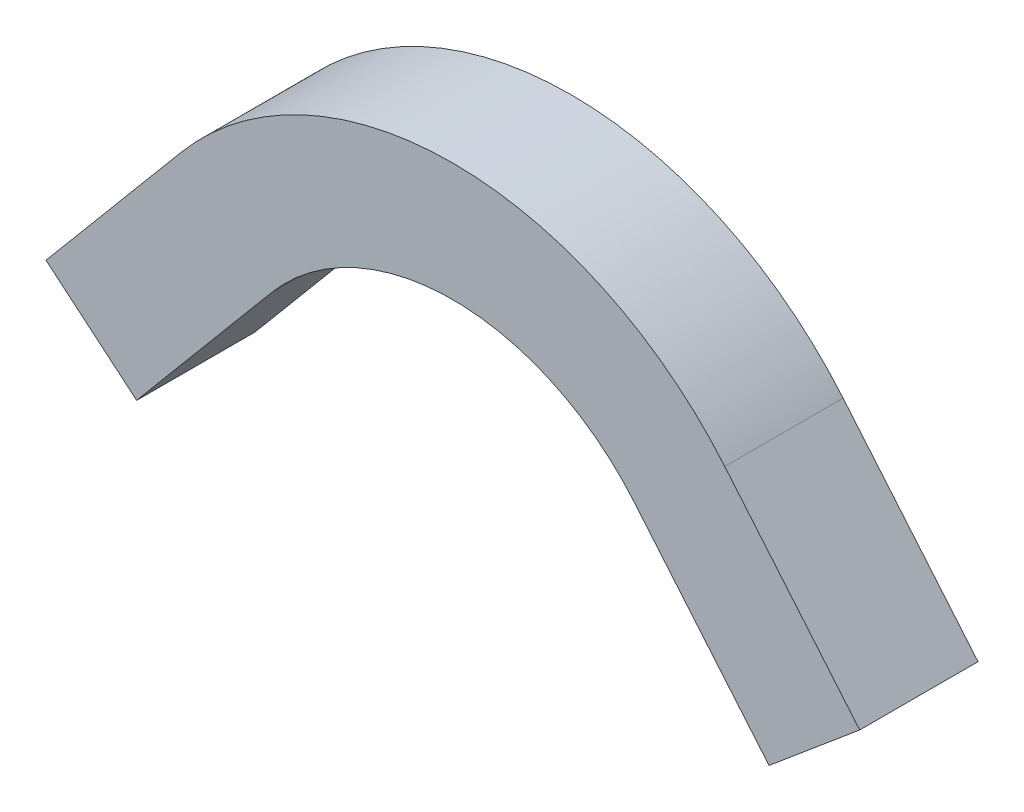
SolidWorks part; units mm, degrees
material "Custom Plastic"
ref_plane "Front Plane" through (0, 0, 0) normal (0, 0, 1) x (1, 0, 0)
ref_plane "Top Plane" through (0, 0, 0) normal (0, 1, 0) x (1, 0, 0)
ref_plane "Right Plane" through (0, 0, 0) normal (1, 0, 0) x (0, 0, -1)
sketch "Sketch1" plane through (0, 0, 0) normal (0, 0, 1) x (1, 0, 0)
  line L0 (-38.3022, 32.1394) -> (0, 0) construction
  line L1 (0, 0) -> (0, 50) construction
  line L2 (38.3022, 32.1394) -> (0, 0) construction
  line L3 (45.9627, 38.5673) -> (30.6418, 25.7115)
  line L4 (-45.9627, 38.5673) -> (-30.6418, 25.7115)
  line L5 (-38.3022, 32.1394) -> (0, 77.7862) construction
  line L6 (-38.3022, 32.1394) -> (0, 32.1394) construction
  arc A0 (38.3022, 32.1394) -> (-38.3022, 32.1394) centre (0, 0) ccw construction
  arc A1 (45.9627, 38.5673) -> (-45.9627, 38.5673) centre (0, 0) ccw
  arc A2 (30.6418, 25.7115) -> (-30.6418, 25.7115) centre (0, 0) ccw
  point P11 (0, 0)
  point P13 (0, 0)
  dimension "D1" = 100
  dimension "D2" = 50
  dimension "D3" = 10
  dimension "D4" = 10
extrude "Boss-Extrude1" add sketch "Sketch1" along normal mid plane 20
ref_plane "Plane1" through (0, 0, 0) normal (-1, 0, 0) x (0, 0, 1)
sketch "Sketch2" plane through (0, 0, 0) normal (-0.6428, -0.766, 0) x (0, 0, 1)
  line L1 (10, 60) -> (-10, 60)
  line L2 (10, 60) -> (10, 40)
  line L3 (10, 40) -> (-10, 40)
  line L4 (-10, 60) -> (-10, 40)
extrude "Boss-Extrude2" add sketch "Sketch2" along normal blind 26.2
mirror "Mirror1" about plane through (0, 0, 0) normal (-1, 0, 0) of "Boss-Extrude2"
sketch "Sketch3" plane through (0, 0, -10) normal (0, 0, -1) x (-1, 0, 0)
  line L0 (47.4828, 5.6411) -> (62.8037, 18.4969)
  line L1 (47.4828, 5.6411) -> (53.4441, -1.4633)
  line L2 (62.8037, 18.4969) -> (68.765, 11.3925)
  line L3 (53.4441, -1.4633) -> (68.765, 11.3925)
  line L5 (0, 60) -> (0, 40) construction
  line L6 (-53.4441, -1.4633) -> (-68.765, 11.3925)
  line L7 (-62.8037, 18.4969) -> (-68.765, 11.3925)
  line L8 (-47.4828, 5.6411) -> (-53.4441, -1.4633)
  line L9 (-47.4828, 5.6411) -> (-62.8037, 18.4969)
  arc A0 (45.9627, 38.5673) -> (-45.9627, 38.5673) centre (0, 0) ccw construction
  arc A1 (30.6418, 25.7115) -> (-30.6418, 25.7115) centre (0, 0) ccw construction
  dimension "D1" = 9.2742
extrude "Boss-Extrude3" add sketch "Sketch3" against normal up to surface (20 mm away) up to face at (0, 26.5694, 10)
